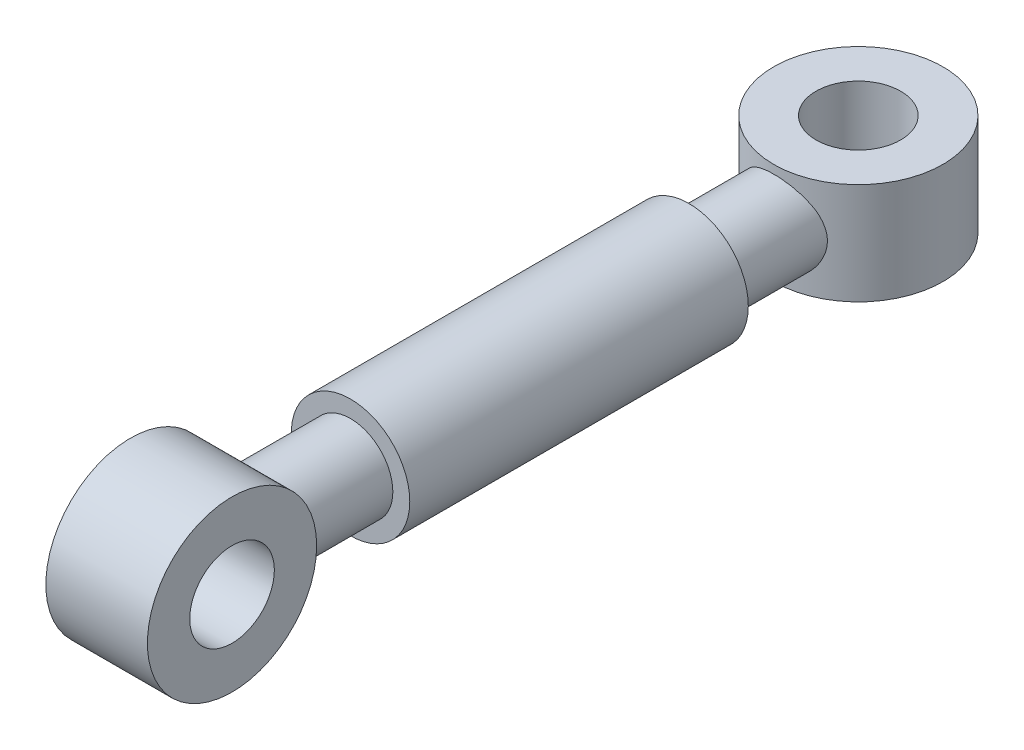
SolidWorks part; units mm, degrees
ref_plane "Front Plane" through (0, 0, 0) normal (0, 0, 1) x (1, 0, 0)
ref_plane "Top Plane" through (0, 0, 0) normal (0, 1, 0) x (1, 0, 0)
ref_plane "Right Plane" through (0, 0, 0) normal (1, 0, 0) x (0, 0, -1)
sketch "Sketch2" plane through (0, 0, 0) normal (0, 0, 1) x (1, 0, 0)
  circle A0 centre (0, 0) radius 1.75
  dimension "D1" = 3.5
extrude "Boss-Extrude1" add sketch "Sketch2" along normal mid plane 10
sketch "Sketch3" plane through (0, 0, 0) normal (0, 0, 1) x (1, 0, 0)
  circle A0 centre (0, 0) radius 1.25
extrude "Boss-Extrude2" add sketch "Sketch3" along normal mid plane 17
sketch "Sketch4" plane through (0, 0, 0) normal (0, 1, 0) x (1, 0, 0)
  circle A0 centre (0, 10) radius 2.5
  circle A2 centre (0, 10) radius 1.25
extrude "Boss-Extrude3" add sketch "Sketch4" along normal mid plane 3 separate body
sketch "Sketch5" plane through (0, 0, 0) normal (1, 0, 0) x (0, 0, -1)
  circle A0 centre (-10, 0) radius 2.5
  circle A1 centre (-10, 0) radius 1.25
extrude "Boss-Extrude4" add sketch "Sketch5" along normal mid plane 3
